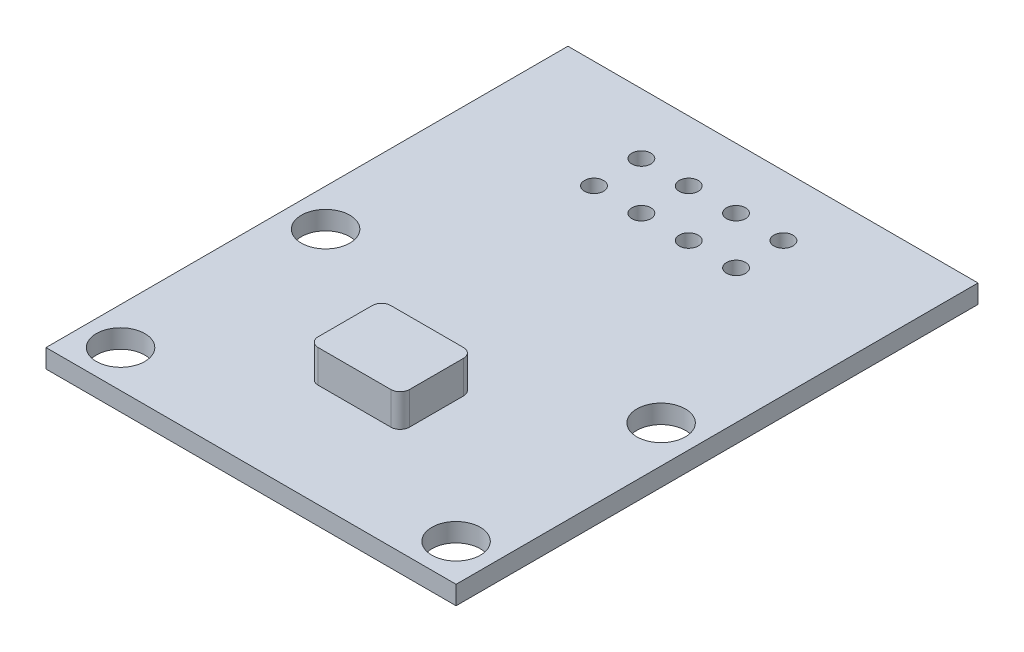
SolidWorks part; units mm, degrees
ref_plane "Front Plane" through (0, 0, 0) normal (0, 0, 1) x (1, 0, 0)
ref_plane "Top Plane" through (0, 0, 0) normal (0, 1, 0) x (1, 0, 0)
ref_plane "Right Plane" through (0, 0, 0) normal (1, 0, 0) x (0, 0, -1)
sketch "Sketch1" plane through (0, 0, 0) normal (0, 1, 0) x (1, 0, 0)
  line L0 (13.4498, 7.5) -> (-1.1687, 7.5) construction
  line L1 (0, 0) -> (22, 0)
  line L2 (0, 0) -> (0, 28)
  line L3 (0, 28) -> (22, 28)
  line L4 (22, 0) -> (22, 28)
  line L5 (8.55, 9.45) -> (13.45, 9.45) construction
  line L6 (8.55, 9.45) -> (8.55, 5.55) construction
  line L7 (8.55, 5.55) -> (13.45, 5.55) construction
  line L8 (13.45, 9.45) -> (13.45, 5.55) construction
  line L9 (9.73, 24.75) -> (12.27, 24.75) construction
  line L10 (12.27, 24.75) -> (12.27, 29.0851) construction
  circle A0 centre (2, 2) radius 1.3
  circle A1 centre (20, 2) radius 1.3
  circle A2 centre (20, 13) radius 1.3
  circle A3 centre (2, 13) radius 1.3
  circle A4 centre (14.81, 24.75) radius 0.51
  circle A5 centre (14.81, 22.21) radius 0.51
  circle A6 centre (12.27, 24.75) radius 0.51
  circle A7 centre (9.73, 24.75) radius 0.51
  circle A8 centre (7.19, 24.75) radius 0.51
  circle A9 centre (12.27, 22.21) radius 0.51
  circle A10 centre (9.73, 22.21) radius 0.51
  circle A11 centre (7.19, 22.21) radius 0.51
  point P13 (11, 5.55)
  point P14 (11, 0)
  point P15 (13.45, 7.5)
  point P25 (11, 24.75)
  point P32 (11, 28)
  dimension "D3" = 2.6
  dimension "D4" = 11
  dimension "D12" = 2.54
  dimension "D13" = 1.02
  dimension "D1" = 28
  dimension "D2" = 22
  dimension "D5" = 18
  dimension "D6" = 2
  dimension "D7" = 2
  dimension "D8" = 2
  dimension "D9" = 4.9
  dimension "D10" = 3.9
  dimension "D11" = 7.5
  dimension "D14" = 17.25
  dimension "D17" = 2.54
  dimension "D15" = 4
  dimension "D16" = 4
extrude "Boss-Extrude1" add sketch "Sketch1" along normal blind 1
sketch "Sketch2" plane through (0, 1, 0) normal (0, 1, 0) x (1, 0, 0)
  line L0 (0, 0) -> (22, 0) construction
  line L1 (9.05, 9.45) -> (12.95, 9.45)
  line L2 (8.55, 8.95) -> (8.55, 6.05)
  line L3 (9.05, 5.55) -> (12.95, 5.55)
  line L4 (13.45, 8.95) -> (13.45, 6.05)
  line L5 (13.264, 7.5) -> (-0.091, 7.5) construction
  arc A0 (8.55, 6.05) -> (9.05, 5.55) centre (9.05, 6.05) ccw
  arc A1 (13.45, 6.05) -> (12.95, 5.55) centre (12.95, 6.05) cw
  arc A2 (13.45, 8.95) -> (12.95, 9.45) centre (12.95, 8.95) ccw
  arc A3 (9.05, 9.45) -> (8.55, 8.95) centre (9.05, 8.95) ccw
  point P8 (13.45, 7.5)
  point P9 (11, 0)
  point P10 (11, 5.55)
  point P15 (13.45, 5.55)
  point P18 (13.45, 9.45)
  point P21 (8.55, 9.45)
  dimension "D4" = 0.5
  dimension "D1" = 3.9
  dimension "D2" = 4.9
  dimension "D3" = 7.5
extrude "Boss-Extrude2" add sketch "Sketch2" along normal blind 1.75
